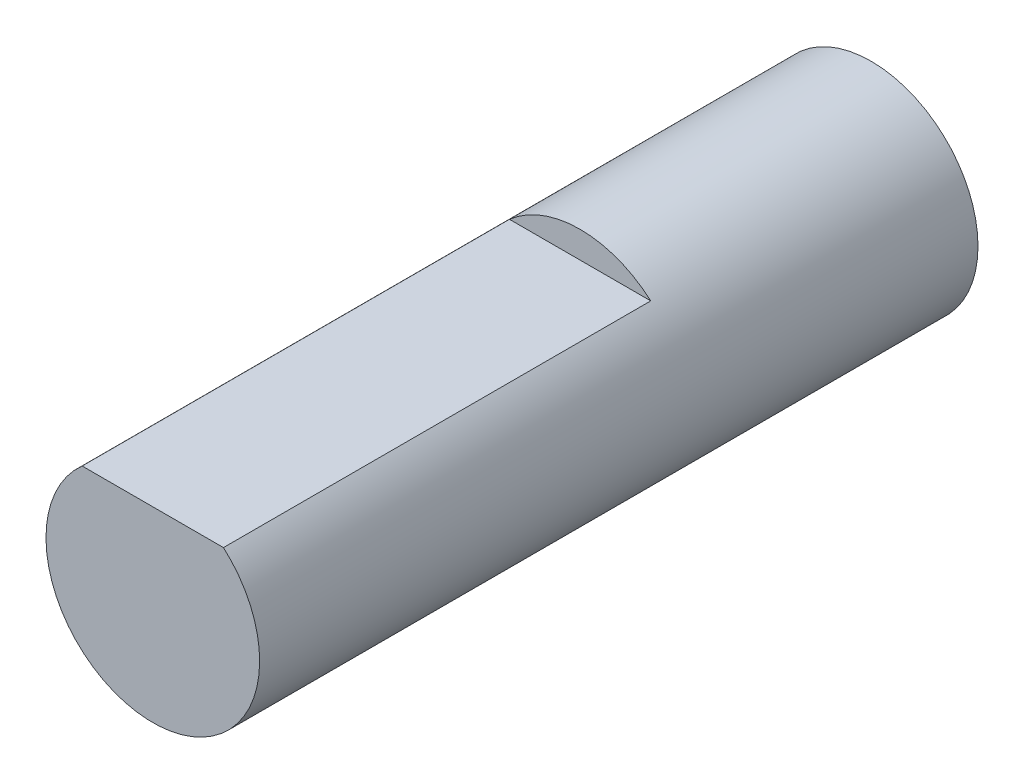
SolidWorks part; units mm, degrees
ref_plane "Front Plane" through (0, 0, 0) normal (0, 0, 1) x (1, 0, 0)
ref_plane "Top Plane" through (0, 0, 0) normal (0, 1, 0) x (1, 0, 0)
ref_plane "Right Plane" through (0, 0, 0) normal (1, 0, 0) x (0, 0, -1)
sketch "S01 - Round root of motor shaft" plane through (0, 0, 0) normal (0, 0, 1) x (1, 0, 0)
  circle A0 centre (0, 0) radius 2
  dimension "D1" = 4
extrude "01 - Round root of motor shaft" add sketch "S01 - Round root of motor shaft" along normal blind 5.45 from offset 0.95
sketch "S02 - 4 mm shaft with 3.5 mm across flat" plane through (0, 0, 0) normal (0, 0, 1) x (1, 0, 0)
  line L0 (-1.3229, 1.5) -> (1.3229, 1.5)
  arc A0 (1.3229, 1.5) -> (-1.3229, 1.5) centre (0, 0) cw
  dimension "D1" = 2
  dimension "D2" = 1.3229
extrude "02 - 4 mm shaft with 3.5 mm across flat" add sketch "S02 - 4 mm shaft with 3.5 mm across flat" along normal blind 8 from offset 4.5
